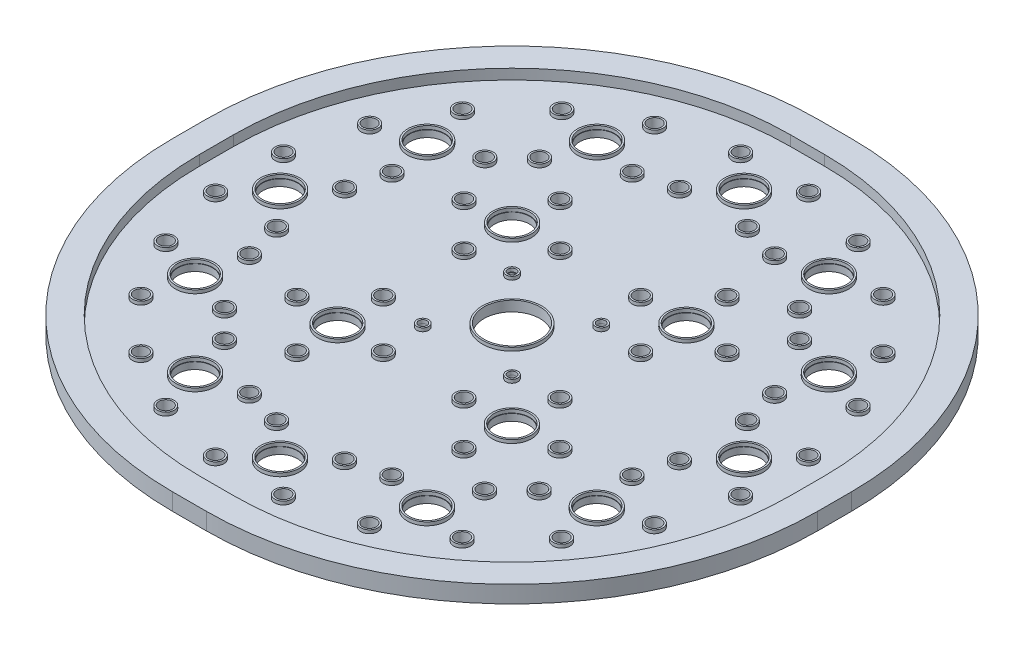
SolidWorks part; units mm, degrees
ref_plane "Front Plane" through (0, 0, 0) normal (0, 0, 1) x (1, 0, 0)
ref_plane "Top Plane" through (0, 0, 0) normal (0, 1, 0) x (1, 0, 0)
ref_plane "Right Plane" through (0, 0, 0) normal (1, 0, 0) x (0, 0, -1)
sketch "Sketch1" plane through (0, 0, 0) normal (0, 1, 0) x (1, 0, 0)
  line L0 (0, 0) -> (-80, 0) construction
  line L2 (0, 0) -> (0, 15) construction
  line L3 (-15, 15) -> (15, 15) construction
  line L7 (-80, 12.8) -> (-80, -12.7) construction
  line L73 (-80, 0) -> (-56.6, 0.05) construction
  line L74 (-80, 12.8) -> (-56.6, 12.8) construction
  line L75 (-68.3, 10.029) -> (-59.3, 10.029) construction
  line L76 (-59.3, 10.029) -> (-59.3, -9.971) construction
  line L77 (-59.3, -9.971) -> (-77.3, -9.971) construction
  line L78 (-56.6, 12.8) -> (-56.6, -12.7) construction
  line L79 (-56.6, -12.7) -> (-80, -12.7) construction
  line L80 (-62.882, 51.0851) -> (-75.632, 29.0015) construction
  line L81 (-15, 15) -> (-15, -15) construction
  line L82 (-15, -15) -> (15, -15) construction
  line L83 (15, 15) -> (15, -15) construction
  line L84 (-38.7699, -24.5868) -> (-26.042, -11.8589) construction
  line L85 (-56.3408, 21.0148) -> (-71.9293, 30.0148) construction
  line L86 (-55.367, 17.3015) -> (-75.632, 29.0015) construction
  line L87 (-46.3408, 38.3353) -> (-56.3408, 21.0148) construction
  line L88 (-42.617, 39.3851) -> (-55.367, 17.3015) construction
  line L89 (-54.135, 42.8353) -> (-46.3408, 38.3353) construction
  line L90 (-62.882, 51.0851) -> (-42.617, 39.3851) construction
  line L91 (-28.9149, 75.682) -> (-50.9985, 62.932) construction
  line L92 (-38.2852, 46.3698) -> (-47.2852, 61.9582) construction
  line L93 (-39.2985, 42.667) -> (-50.9985, 62.932) construction
  line L94 (-20.9647, 56.3698) -> (-38.2852, 46.3698) construction
  line L95 (-17.2149, 55.417) -> (-39.2985, 42.667) construction
  line L96 (-25.4647, 64.164) -> (-20.9647, 56.3698) construction
  line L97 (-28.9149, 75.682) -> (-17.2149, 55.417) construction
  line L98 (12.8, 80) -> (-12.7, 80) construction
  line L99 (-9.971, 59.3) -> (-9.971, 77.3) construction
  line L100 (-12.7, 56.6) -> (-12.7, 80) construction
  line L101 (10.029, 59.3) -> (-9.971, 59.3) construction
  line L102 (12.8, 56.6) -> (-12.7, 56.6) construction
  line L103 (10.029, 68.3) -> (10.029, 59.3) construction
  line L104 (12.8, 80) -> (12.8, 56.6) construction
  line L105 (51.0851, 62.882) -> (29.0015, 75.632) construction
  line L106 (21.0148, 56.3408) -> (30.0148, 71.9293) construction
  line L107 (17.3015, 55.367) -> (29.0015, 75.632) construction
  line L108 (38.3353, 46.3408) -> (21.0148, 56.3408) construction
  line L109 (39.3851, 42.617) -> (17.3015, 55.367) construction
  line L110 (42.8353, 54.135) -> (38.3353, 46.3408) construction
  line L111 (51.0851, 62.882) -> (39.3851, 42.617) construction
  line L112 (75.682, 28.9149) -> (62.932, 50.9985) construction
  line L113 (46.3698, 38.2852) -> (61.9582, 47.2852) construction
  line L114 (42.667, 39.2985) -> (62.932, 50.9985) construction
  line L115 (56.3698, 20.9647) -> (46.3698, 38.2852) construction
  line L116 (55.417, 17.2149) -> (42.667, 39.2985) construction
  line L117 (64.164, 25.4647) -> (56.3698, 20.9647) construction
  line L118 (75.682, 28.9149) -> (55.417, 17.2149) construction
  line L119 (80, -12.8) -> (80, 12.7) construction
  line L120 (59.3, 9.971) -> (77.3, 9.971) construction
  line L121 (56.6, 12.7) -> (80, 12.7) construction
  line L122 (59.3, -10.029) -> (59.3, 9.971) construction
  line L123 (56.6, -12.8) -> (56.6, 12.7) construction
  line L124 (68.3, -10.029) -> (59.3, -10.029) construction
  line L125 (80, -12.8) -> (56.6, -12.8) construction
  line L126 (62.882, -51.0851) -> (75.632, -29.0015) construction
  line L127 (56.3408, -21.0148) -> (71.9293, -30.0148) construction
  line L128 (55.367, -17.3015) -> (75.632, -29.0015) construction
  line L129 (46.3408, -38.3353) -> (56.3408, -21.0148) construction
  line L130 (42.617, -39.3851) -> (55.367, -17.3015) construction
  line L131 (54.135, -42.8353) -> (46.3408, -38.3353) construction
  line L132 (62.882, -51.0851) -> (42.617, -39.3851) construction
  line L133 (28.9149, -75.682) -> (50.9985, -62.932) construction
  line L134 (38.2852, -46.3698) -> (47.2852, -61.9582) construction
  line L135 (39.2985, -42.667) -> (50.9985, -62.932) construction
  line L136 (20.9647, -56.3698) -> (38.2852, -46.3698) construction
  line L137 (17.2149, -55.417) -> (39.2985, -42.667) construction
  line L138 (25.4647, -64.164) -> (20.9647, -56.3698) construction
  line L139 (28.9149, -75.682) -> (17.2149, -55.417) construction
  line L140 (-12.8, -80) -> (12.7, -80) construction
  line L141 (9.971, -59.3) -> (9.971, -77.3) construction
  line L142 (12.7, -56.6) -> (12.7, -80) construction
  line L143 (-10.029, -59.3) -> (9.971, -59.3) construction
  line L144 (-12.8, -56.6) -> (12.7, -56.6) construction
  line L145 (-10.029, -68.3) -> (-10.029, -59.3) construction
  line L146 (-12.8, -80) -> (-12.8, -56.6) construction
  line L147 (-51.0851, -62.882) -> (-29.0015, -75.632) construction
  line L148 (-21.0148, -56.3408) -> (-30.0148, -71.9293) construction
  line L149 (-17.3015, -55.367) -> (-29.0015, -75.632) construction
  line L150 (-38.3353, -46.3408) -> (-21.0148, -56.3408) construction
  line L151 (-39.3851, -42.617) -> (-17.3015, -55.367) construction
  line L152 (-42.8353, -54.135) -> (-38.3353, -46.3408) construction
  line L153 (-51.0851, -62.882) -> (-39.3851, -42.617) construction
  line L154 (-75.682, -28.9149) -> (-62.932, -50.9985) construction
  line L155 (-46.3698, -38.2852) -> (-61.9582, -47.2852) construction
  line L156 (-42.667, -39.2985) -> (-62.932, -50.9985) construction
  line L157 (-56.3698, -20.9647) -> (-46.3698, -38.2852) construction
  line L158 (-55.417, -17.2149) -> (-42.667, -39.2985) construction
  line L159 (-64.164, -25.4647) -> (-56.3698, -20.9647) construction
  line L160 (-75.682, -28.9149) -> (-55.417, -17.2149) construction
  line L161 (-25.6857, -25.6503) -> (-32.7595, -18.5764) construction
  line L162 (0, 0) -> (0, -90) construction
  line L164 (-7.9903, 26.0922) -> (-26.0215, 8.061) construction
  line L165 (-24.5366, 42.6385) -> (-7.9903, 26.0922) construction
  line L166 (-24.5366, 42.6385) -> (-42.5678, 24.6073) construction
  line L167 (-26.0215, 8.061) -> (-42.5678, 24.6073) construction
  line L168 (-5, -5) -> (-95, -5) construction
  line L169 (-95, 5) -> (-5, 5) construction
  line L170 (5, 95) -> (5, 5) construction
  line L172 (26.0922, 7.9903) -> (8.061, 26.0215) construction
  line L173 (42.6385, 24.5366) -> (26.0922, 7.9903) construction
  line L174 (42.6385, 24.5366) -> (24.6073, 42.5678) construction
  line L175 (8.061, 26.0215) -> (24.6073, 42.5678) construction
  line L176 (95, -5) -> (5, -5) construction
  line L177 (13.135, 13.135) -> (13.135, -13.135) construction
  line L178 (13.135, -13.135) -> (-13.135, -13.135) construction
  line L179 (-13.135, -13.135) -> (-13.135, 12.8) construction
  line L180 (-13.135, 12.8) -> (13.135, 13.135) construction
  line L181 (-5, 5) -> (-5, 95) construction
  line L182 (-5, -95) -> (-5, -5) construction
  line L183 (-95, -5) -> (-95, 5)
  line L184 (7.9903, -26.0922) -> (26.0215, -8.061) construction
  line L185 (24.5366, -42.6385) -> (7.9903, -26.0922) construction
  line L186 (24.5366, -42.6385) -> (42.5678, -24.6073) construction
  line L187 (26.0215, -8.061) -> (42.5678, -24.6073) construction
  line L188 (5, 5) -> (95, 5) construction
  line L189 (0, 0) -> (5, 0) construction
  line L192 (-26.0922, -7.9903) -> (-8.061, -26.0215) construction
  line L193 (-42.6385, -24.5366) -> (-26.0922, -7.9903) construction
  line L194 (-42.6385, -24.5366) -> (-24.6073, -42.5678) construction
  line L195 (-8.061, -26.0215) -> (-24.6073, -42.5678) construction
  line L197 (5, 0) -> (5, 5) construction
  line L199 (-5, -95) -> (5, -95)
  line L200 (95, -5) -> (95, 5)
  line L202 (5, 5) -> (-5, 5) construction
  line L203 (-5, 5) -> (-5, -5) construction
  line L204 (-5, -5) -> (5, -5) construction
  line L205 (5, -5) -> (5, 5) construction
  line L206 (5, -5) -> (5, -95) construction
  line L207 (-5, 95) -> (5, 95)
  line L213 (-95, -5) -> (-95, 5) construction
  line L214 (-5, 95) -> (5, 95) construction
  line L215 (95, 5) -> (95, -5) construction
  line L216 (5, -95) -> (-5, -95) construction
  circle A2 centre (-68.3, 0.025) radius 5.125
  circle A3 centre (-59.3, 10.029) radius 2
  circle A4 centre (-59.3, -9.971) radius 2
  circle A5 centre (-77.3, -9.971) radius 2
  circle A6 centre (-77.3, 10.029) radius 2
  circle A7 centre (-61.9293, 47.3353) radius 2
  circle A8 centre (-59.137, 34.1717) radius 5.125
  circle A9 centre (-71.9293, 30.0148) radius 2
  circle A10 centre (-56.3408, 21.0148) radius 2
  circle A11 centre (-46.3408, 38.3353) radius 2
  circle A12 centre (-29.9647, 71.9582) radius 2
  circle A13 centre (-34.1283, 59.162) radius 5.125
  circle A14 centre (-47.2852, 61.9582) radius 2
  circle A15 centre (-38.2852, 46.3698) radius 2
  circle A16 centre (-20.9647, 56.3698) radius 2
  circle A17 centre (10.029, 77.3) radius 2
  circle A18 centre (0.025, 68.3) radius 5.125
  circle A19 centre (-9.971, 77.3) radius 2
  circle A20 centre (-9.971, 59.3) radius 2
  circle A21 centre (10.029, 59.3) radius 2
  circle A22 centre (47.3353, 61.9293) radius 2
  circle A23 centre (34.1717, 59.137) radius 5.125
  circle A24 centre (30.0148, 71.9293) radius 2
  circle A25 centre (21.0148, 56.3408) radius 2
  circle A26 centre (38.3353, 46.3408) radius 2
  circle A27 centre (71.9582, 29.9647) radius 2
  circle A28 centre (59.162, 34.1283) radius 5.125
  circle A29 centre (61.9582, 47.2852) radius 2
  circle A30 centre (46.3698, 38.2852) radius 2
  circle A31 centre (56.3698, 20.9647) radius 2
  circle A32 centre (77.3, -10.029) radius 2
  circle A33 centre (68.3, -0.025) radius 5.125
  circle A34 centre (77.3, 9.971) radius 2
  circle A35 centre (59.3, 9.971) radius 2
  circle A36 centre (59.3, -10.029) radius 2
  circle A37 centre (61.9293, -47.3353) radius 2
  circle A38 centre (59.137, -34.1717) radius 5.125
  circle A39 centre (71.9293, -30.0148) radius 2
  circle A40 centre (56.3408, -21.0148) radius 2
  circle A41 centre (46.3408, -38.3353) radius 2
  circle A42 centre (29.9647, -71.9582) radius 2
  circle A43 centre (34.1283, -59.162) radius 5.125
  circle A44 centre (47.2852, -61.9582) radius 2
  circle A45 centre (38.2852, -46.3698) radius 2
  circle A46 centre (20.9647, -56.3698) radius 2
  circle A47 centre (-10.029, -77.3) radius 2
  circle A48 centre (-0.025, -68.3) radius 5.125
  circle A49 centre (9.971, -77.3) radius 2
  circle A50 centre (9.971, -59.3) radius 2
  circle A51 centre (-10.029, -59.3) radius 2
  circle A52 centre (-47.3353, -61.9293) radius 2
  circle A53 centre (-34.1717, -59.137) radius 5.125
  circle A54 centre (-30.0148, -71.9293) radius 2
  circle A55 centre (-21.0148, -56.3408) radius 2
  circle A56 centre (-38.3353, -46.3408) radius 2
  circle A57 centre (-71.9582, -29.9647) radius 2
  circle A58 centre (-59.162, -34.1283) radius 5.125
  circle A59 centre (-61.9582, -47.2852) radius 2
  circle A60 centre (-46.3698, -38.2852) radius 2
  circle A61 centre (-56.3698, -20.9647) radius 2
  circle A83 centre (-13.135, -13.135) radius 1.25
  circle A84 centre (13.135, -13.135) radius 1.25
  circle A85 centre (13.135, 13.135) radius 1.25
  circle A86 centre (-13.135, 12.8) radius 1.25
  circle A91 centre (-11.8589, 26.042) radius 2
  circle A92 centre (-24.5868, 38.7699) radius 2
  circle A93 centre (-38.729, 24.6278) radius 2
  circle A94 centre (-26.001, 11.8999) radius 2
  circle A99 centre (26.042, 11.8589) radius 2
  circle A100 centre (38.7699, 24.5868) radius 2
  circle A101 centre (24.6278, 38.729) radius 2
  circle A102 centre (11.8999, 26.001) radius 2
  circle A107 centre (11.8589, -26.042) radius 2
  circle A108 centre (24.5868, -38.7699) radius 2
  circle A109 centre (38.729, -24.6278) radius 2
  circle A110 centre (26.001, -11.8999) radius 2
  circle A115 centre (-26.042, -11.8589) radius 2
  circle A116 centre (-38.7699, -24.5868) radius 2
  circle A117 centre (-24.6278, -38.729) radius 2
  circle A118 centre (-11.8999, -26.001) radius 2
  circle A128 centre (0, 0) radius 8.25
  circle A134 centre (-25.6857, -25.6503) radius 5.125
  circle A135 centre (-25.6503, 25.6857) radius 5.125
  circle A136 centre (25.6857, 25.6503) radius 5.125
  circle A137 centre (25.6503, -25.6857) radius 5.125
  arc A138 (-95, 5) -> (-5, 95) centre (-5, 5) cw
  arc A139 (5, 95) -> (95, 5) centre (5, 5) cw
  arc A140 (95, -5) -> (5, -95) centre (5, -5) cw
  arc A141 (-95, -5) -> (-5, -95) centre (-5, -5) ccw
  point P60 (0, 0)
  point P77 (0, 0)
  point P203 (0, 0)
  point P211 (0, 0)
  point P232 (0, 0)
  point P234 (0, 0)
  point P254 (0, 0)
  point P259 (0, 0)
  point P287 (0, 0)
  point P301 (0, 0)
  point P315 (0, 0)
  dimension "D2" = 16.5
  dimension "D3" = 10.25
  dimension "D11" = 26.27
  dimension "D13" = 4
  dimension "D15" = 26.27
  dimension "D16" = 5
  dimension "D8" = 90
  dimension "D9" = 15
  dimension "D10" = 2.5
  dimension "D17" = 90
  dimension "D19" = 4
  dimension "D6" = 4
  dimension "D22" = 10.25
  dimension "D23" = 4
  dimension "D24" = 4
  dimension "D4" = 12
  dimension "D5" = 80
  dimension "D12" = 20
  dimension "D14" = 18
  dimension "D18" = 30
  dimension "D7" = 5
extrude "Boss-Extrude2" add sketch "Sketch1" along normal blind 2
sketch "Sketch2" plane through (0, 2, 0) normal (0, 1, 0) x (1, 0, 0)
  line L5 (-95, -5) -> (-95, 5)
  line L6 (-5, -95) -> (5, -95)
  line L7 (95, -5) -> (95, 5)
  line L8 (-87, 5) -> (-87, -5)
  line L9 (5, 87) -> (-5, 87)
  line L10 (87, -5) -> (87, 5)
  line L11 (-5, -87) -> (5, -87)
  line L12 (-87, 5) -> (-87, -5)
  line L13 (5, 87) -> (-5, 87)
  line L14 (87, -5) -> (87, 5)
  line L15 (-5, -87) -> (5, -87)
  line L16 (95, -5) -> (95, 5) construction
  line L17 (-5, 95) -> (5, 95)
  arc A0 (-95, -5) -> (-5, -95) centre (-5, -5) ccw
  arc A1 (-95, -5) -> (-5, -95) centre (-5, -5) ccw construction
  arc A4 (95, 5) -> (5, 95) centre (5, 5) ccw construction
  arc A5 (-95, 5) -> (-5, 95) centre (-5, 5) cw
  arc A6 (-5, 95) -> (-95, 5) centre (-5, 5) ccw construction
  arc A7 (95, 5) -> (5, 95) centre (5, 5) ccw
  arc A8 (-5, 87) -> (-87, 5) centre (-5, 5) ccw
  arc A9 (87, 5) -> (5, 87) centre (5, 5) ccw
  arc A10 (5, -87) -> (87, -5) centre (5, -5) ccw
  arc A11 (-87, -5) -> (-5, -87) centre (-5, -5) ccw
  arc A12 (-5, 87) -> (-87, 5) centre (-5, 5) ccw
  arc A13 (87, 5) -> (5, 87) centre (5, 5) ccw
  arc A14 (5, -87) -> (87, -5) centre (5, -5) ccw
  arc A15 (-87, -5) -> (-5, -87) centre (-5, -5) ccw
  arc A16 (5, -95) -> (95, -5) centre (5, -5) ccw
  arc A17 (5, -95) -> (95, -5) centre (5, -5) ccw construction
  dimension "D1" = 8
extrude "Boss-Extrude3" add sketch "Sketch2" along normal blind 3 contours L6 A16 L7 A7 L17 A5 L5 A0 A15 L12 A12 L13 A13 L14 A14 L15
sketch "Sketch3" plane through (0, 2, 0) normal (0, 1, 0) x (1, 0, 0)
  circle A0 centre (-59.162, -34.1283) radius 5.75
  circle A1 centre (-68.3, 0.025) radius 5.75
  circle A2 centre (-59.137, 34.1717) radius 5.75
  circle A3 centre (-34.1283, 59.162) radius 5.75
  circle A4 centre (0.025, 68.3) radius 5.75
  circle A5 centre (34.1717, 59.137) radius 5.75
  circle A6 centre (59.162, 34.1283) radius 5.75
  circle A7 centre (68.3, -0.025) radius 5.75
  circle A8 centre (59.137, -34.1717) radius 5.75
  circle A9 centre (34.1283, -59.162) radius 5.75
  circle A10 centre (-0.025, -68.3) radius 5.75
  circle A11 centre (-34.1717, -59.137) radius 5.75
  circle A12 centre (-25.6857, -25.6503) radius 5.75
  circle A13 centre (-25.6503, 25.6857) radius 5.75
  circle A14 centre (25.6857, 25.6503) radius 5.75
  circle A15 centre (25.6503, -25.6857) radius 5.75
  circle A16 centre (-56.3698, -20.9647) radius 2
  circle A17 centre (-25.6857, -25.6503) radius 5.25
  circle A18 centre (-25.6503, 25.6857) radius 5.25
  circle A19 centre (25.6857, 25.6503) radius 5.25
  circle A20 centre (25.6503, -25.6857) radius 5.25
  circle A21 centre (-59.162, -34.1283) radius 5.25
  circle A22 centre (-68.3, 0.025) radius 5.25
  circle A23 centre (-59.137, 34.1717) radius 5.25
  circle A24 centre (-34.1283, 59.162) radius 5.25
  circle A25 centre (0.025, 68.3) radius 5.25
  circle A26 centre (34.1717, 59.137) radius 5.25
  circle A27 centre (59.162, 34.1283) radius 5.25
  circle A28 centre (68.3, -0.025) radius 5.25
  circle A29 centre (59.137, -34.1717) radius 5.25
  circle A30 centre (34.1283, -59.162) radius 5.25
  circle A31 centre (-0.025, -68.3) radius 5.25
  circle A32 centre (-34.1717, -59.137) radius 5.25
  circle A33 centre (-56.3698, -20.9647) radius 2.5
  circle A34 centre (0, 0) radius 8.25
  circle A35 centre (0, 0) radius 8.75
  circle A36 centre (-46.3698, -38.2852) radius 2
  circle A37 centre (-46.3698, -38.2852) radius 2.5
  circle A38 centre (-71.9582, -29.9647) radius 2.5
  circle A39 centre (-71.9582, -29.9647) radius 2
  circle A40 centre (-61.9582, -47.2852) radius 2.5
  circle A41 centre (-61.9582, -47.2852) radius 2
  circle A42 centre (-77.3, -9.971) radius 2.5
  circle A43 centre (-77.3, -9.971) radius 2
  circle A44 centre (-59.3, -9.971) radius 2.5
  circle A45 centre (-59.3, -9.971) radius 2
  circle A46 centre (-59.3, 10.029) radius 2
  circle A47 centre (-59.3, 10.029) radius 2.5
  circle A48 centre (-77.3, 10.029) radius 2
  circle A49 centre (-77.3, 10.029) radius 2.5
  circle A50 centre (-71.9293, 30.0148) radius 2.5
  circle A51 centre (-71.9293, 30.0148) radius 2
  circle A52 centre (-56.3408, 21.0148) radius 2.5
  circle A53 centre (-56.3408, 21.0148) radius 2
  circle A54 centre (-46.3408, 38.3353) radius 2
  circle A55 centre (-46.3408, 38.3353) radius 2.5
  circle A56 centre (-61.9293, 47.3353) radius 2
  circle A57 centre (-61.9293, 47.3353) radius 2.5
  circle A58 centre (-47.2852, 61.9582) radius 2.5
  circle A59 centre (-47.2852, 61.9582) radius 2
  circle A60 centre (-38.2852, 46.3698) radius 2.5
  circle A61 centre (-38.2852, 46.3698) radius 2
  circle A62 centre (-20.9647, 56.3698) radius 2
  circle A63 centre (-20.9647, 56.3698) radius 2.5
  circle A64 centre (-29.9647, 71.9582) radius 2
  circle A65 centre (-29.9647, 71.9582) radius 2.5
  circle A66 centre (-9.971, 77.3) radius 2.5
  circle A67 centre (-9.971, 77.3) radius 2
  circle A68 centre (-9.971, 59.3) radius 2.5
  circle A69 centre (-9.971, 59.3) radius 2
  circle A70 centre (10.029, 59.3) radius 2
  circle A71 centre (10.029, 59.3) radius 2.5
  circle A72 centre (10.029, 77.3) radius 2
  circle A73 centre (10.029, 77.3) radius 2.5
  circle A74 centre (30.0148, 71.9293) radius 2.5
  circle A75 centre (30.0148, 71.9293) radius 2
  circle A76 centre (21.0148, 56.3408) radius 2.5
  circle A77 centre (21.0148, 56.3408) radius 2
  circle A78 centre (38.3353, 46.3408) radius 2
  circle A79 centre (38.3353, 46.3408) radius 2.5
  circle A80 centre (47.3353, 61.9293) radius 2
  circle A81 centre (47.3353, 61.9293) radius 2.5
  circle A82 centre (61.9582, 47.2852) radius 2.5
  circle A83 centre (61.9582, 47.2852) radius 2
  circle A84 centre (46.3698, 38.2852) radius 2.5
  circle A85 centre (46.3698, 38.2852) radius 2
  circle A86 centre (56.3698, 20.9647) radius 2
  circle A87 centre (56.3698, 20.9647) radius 2.5
  circle A88 centre (71.9582, 29.9647) radius 2
  circle A89 centre (71.9582, 29.9647) radius 2.5
  circle A90 centre (77.3, 9.971) radius 2.5
  circle A91 centre (77.3, 9.971) radius 2
  circle A92 centre (59.3, 9.971) radius 2.5
  circle A93 centre (59.3, 9.971) radius 2
  circle A94 centre (59.3, -10.029) radius 2
  circle A95 centre (59.3, -10.029) radius 2.5
  circle A96 centre (77.3, -10.029) radius 2
  circle A97 centre (77.3, -10.029) radius 2.5
  circle A98 centre (71.9293, -30.0148) radius 2.5
  circle A99 centre (71.9293, -30.0148) radius 2
  circle A100 centre (56.3408, -21.0148) radius 2.5
  circle A101 centre (56.3408, -21.0148) radius 2
  circle A102 centre (46.3408, -38.3353) radius 2
  circle A103 centre (46.3408, -38.3353) radius 2.5
  circle A104 centre (61.9293, -47.3353) radius 2
  circle A105 centre (61.9293, -47.3353) radius 2.5
  circle A106 centre (47.2852, -61.9582) radius 2.5
  circle A107 centre (47.2852, -61.9582) radius 2
  circle A108 centre (38.2852, -46.3698) radius 2.5
  circle A109 centre (38.2852, -46.3698) radius 2
  circle A110 centre (20.9647, -56.3698) radius 2
  circle A111 centre (20.9647, -56.3698) radius 2.5
  circle A112 centre (29.9647, -71.9582) radius 2
  circle A113 centre (29.9647, -71.9582) radius 2.5
  circle A114 centre (9.971, -77.3) radius 2.5
  circle A115 centre (9.971, -77.3) radius 2
  circle A116 centre (9.971, -59.3) radius 2.5
  circle A117 centre (9.971, -59.3) radius 2
  circle A118 centre (-10.029, -59.3) radius 2
  circle A119 centre (-10.029, -59.3) radius 2.5
  circle A120 centre (-10.029, -77.3) radius 2
  circle A121 centre (-10.029, -77.3) radius 2.5
  circle A122 centre (-30.0148, -71.9293) radius 2.5
  circle A123 centre (-30.0148, -71.9293) radius 2
  circle A124 centre (-21.0148, -56.3408) radius 2.5
  circle A125 centre (-21.0148, -56.3408) radius 2
  circle A126 centre (-38.3353, -46.3408) radius 2
  circle A127 centre (-38.3353, -46.3408) radius 2.5
  circle A128 centre (-47.3353, -61.9293) radius 2
  circle A129 centre (-47.3353, -61.9293) radius 2.5
  circle A130 centre (-38.7699, -24.5868) radius 2.5
  circle A131 centre (-38.7699, -24.5868) radius 2
  circle A132 centre (-26.042, -11.8589) radius 2.5
  circle A133 centre (-26.042, -11.8589) radius 2
  circle A134 centre (-24.6278, -38.729) radius 2
  circle A135 centre (-24.6278, -38.729) radius 2.5
  circle A136 centre (-11.8999, -26.001) radius 2.5
  circle A137 centre (-11.8999, -26.001) radius 2
  circle A138 centre (-24.5868, 38.7699) radius 2.5
  circle A139 centre (-24.5868, 38.7699) radius 2
  circle A140 centre (-11.8589, 26.042) radius 2.5
  circle A141 centre (-11.8589, 26.042) radius 2
  circle A142 centre (-26.001, 11.8999) radius 2.5
  circle A143 centre (-26.001, 11.8999) radius 2
  circle A144 centre (-38.729, 24.6278) radius 2.5
  circle A145 centre (-38.729, 24.6278) radius 2
  circle A146 centre (38.7699, 24.5868) radius 2.5
  circle A147 centre (38.7699, 24.5868) radius 2
  circle A148 centre (26.042, 11.8589) radius 2.5
  circle A149 centre (26.042, 11.8589) radius 2
  circle A150 centre (11.8999, 26.001) radius 2.5
  circle A151 centre (11.8999, 26.001) radius 2
  circle A152 centre (24.6278, 38.729) radius 2.5
  circle A153 centre (24.6278, 38.729) radius 2
  circle A154 centre (24.5868, -38.7699) radius 2.5
  circle A155 centre (24.5868, -38.7699) radius 2
  circle A156 centre (11.8589, -26.042) radius 2.5
  circle A157 centre (11.8589, -26.042) radius 2
  circle A158 centre (26.001, -11.8999) radius 2.5
  circle A159 centre (26.001, -11.8999) radius 2
  circle A160 centre (38.729, -24.6278) radius 2.5
  circle A161 centre (38.729, -24.6278) radius 2
  circle A162 centre (-13.135, -13.135) radius 1.2351
  circle A163 centre (-13.135, -13.135) radius 1.735
  circle A164 centre (-13.135, 13.135) radius 1.735
  circle A165 centre (-13.135, 13.135) radius 1.2351
  circle A166 centre (13.135, 13.135) radius 1.735
  circle A167 centre (13.135, 13.135) radius 1.2351
  circle A168 centre (13.135, -13.135) radius 1.735
  circle A169 centre (13.135, -13.135) radius 1.2351
  point P27 (0, 0)
  point P38 (0, 0)
  point P45 (0, 0)
  point P70 (0, 0)
  point P222 (0, 0)
  point P276 (0, 0)
  point P290 (0, 0)
  dimension "D1" = 11.5
  dimension "D3" = 11.5
  dimension "D7" = 10.5
  dimension "D8" = 17.5
  dimension "D9" = 16.5
  dimension "D10" = 4
  dimension "D11" = 5
  dimension "D12" = 4
  dimension "D13" = 5
  dimension "D14" = 4
  dimension "D15" = 5
  dimension "D16" = 4
  dimension "D17" = 5
  dimension "D19" = 4
  dimension "D20" = 5
  dimension "D21" = 5
  dimension "D22" = 4
  dimension "D23" = 4
  dimension "D24" = 5
  dimension "D25" = 4
  dimension "D26" = 5
  dimension "D28" = 2.4702
  dimension "D29" = 3.47
  dimension "D2" = 12
  dimension "D4" = 4
  dimension "D5" = 4
  dimension "D6" = 12
  dimension "D18" = 12
  dimension "D27" = 4
  dimension "D30" = 4
extrude "Boss-Extrude7" add sketch "Sketch3" along normal blind 1
